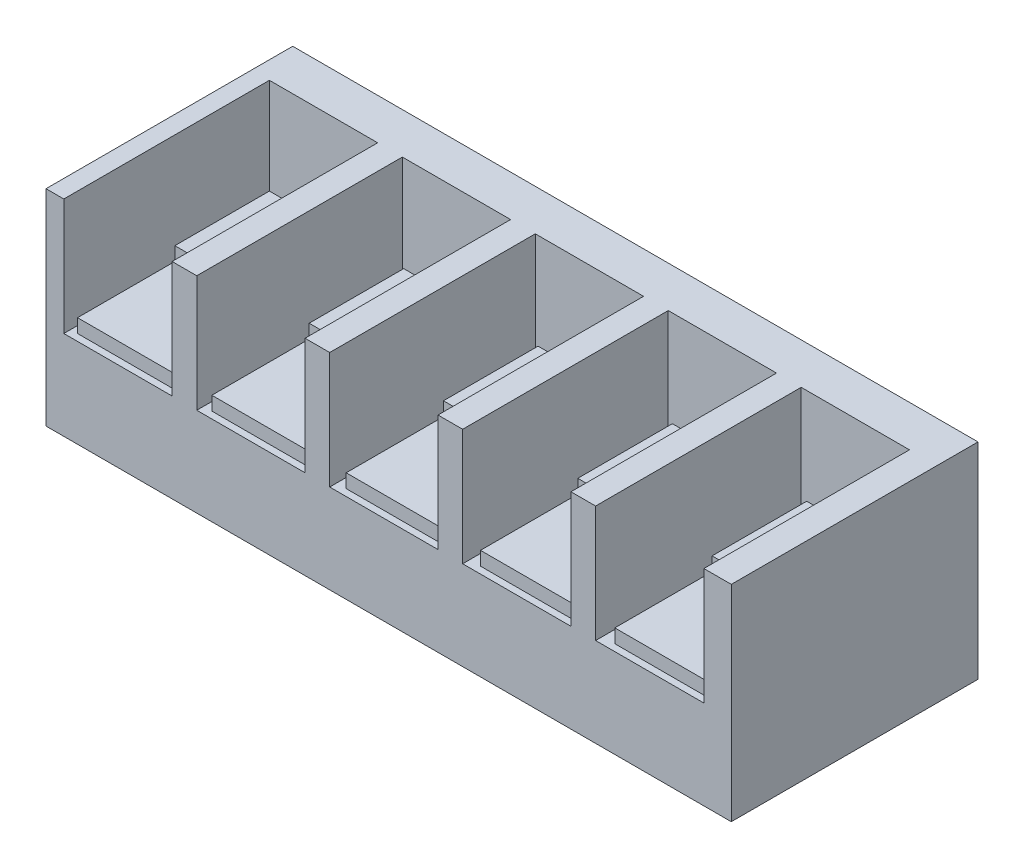
SolidWorks part; units mm, degrees
material "PVC Rigid"
ref_plane "Front Plane" through (0, 0, 0) normal (0, 0, 1) x (1, 0, 0)
ref_plane "Top Plane" through (0, 0, 0) normal (0, 1, 0) x (1, 0, 0)
ref_plane "Right Plane" through (0, 0, 0) normal (1, 0, 0) x (0, 0, -1)
sketch "Sketch1" plane through (0, 0, 0) normal (0, 1, 0) x (1, 0, 0)
  line L1 (25, -9) -> (-25, -9)
  line L2 (25, -9) -> (25, 9)
  line L3 (25, 9) -> (-25, 9)
  line L4 (-25, -9) -> (-25, 9)
  point P0 (0, 0)
  dimension "D1" = 50
  dimension "D2" = 18
extrude "Boss-Extrude1" add sketch "Sketch1" along normal blind 15
sketch "Sketch2" plane through (0, 0, 9) normal (0, 0, 1) x (1, 0, 0)
  line L0 (-25, 15) -> (25, 15) construction
  line L1 (-23.7, 15) -> (-15.8, 15)
  line L2 (-23.7, 15) -> (-23.7, 6.5)
  line L3 (-23.7, 6.5) -> (-15.8, 6.5)
  line L4 (-15.8, 15) -> (-15.8, 6.5)
  line L5 (-25, 15) -> (-25, 0) construction
  line L6 (-14, 15) -> (-6.1, 15)
  line L7 (-14, 15) -> (-14, 6.5)
  line L8 (-14, 6.5) -> (-6.1, 6.5)
  line L9 (-6.1, 15) -> (-6.1, 6.5)
  line L10 (-4.3, 15) -> (3.6, 15)
  line L11 (-4.3, 15) -> (-4.3, 6.5)
  line L12 (-4.3, 6.5) -> (3.6, 6.5)
  line L13 (3.6, 15) -> (3.6, 6.5)
  line L14 (5.4, 15) -> (13.3, 15)
  line L15 (5.4, 15) -> (5.4, 6.5)
  line L16 (5.4, 6.5) -> (13.3, 6.5)
  line L17 (13.3, 15) -> (13.3, 6.5)
  line L18 (15.1, 15) -> (23, 15)
  line L19 (15.1, 15) -> (15.1, 6.5)
  line L20 (15.1, 6.5) -> (23, 6.5)
  line L21 (23, 15) -> (23, 6.5)
  dimension "D1" = 1.3
  dimension "D2" = 7.9
  dimension "D3" = 8.5
  dimension "D4" = 5
extrude "Cut-Extrude1" cut sketch "Sketch2" against normal offset from surface (15 mm away) 3 up to face at (0, 7.5, -9)
sketch "Sketch3" plane through (0, 0, 0) normal (0, -1, 0) x (1, 0, 0)
  line L8 (-23.5, 7.5) -> (-23.5, -7.5)
  line L9 (-23.5, -7.5) -> (23.5, -7.5)
  line L10 (23.5, -7.5) -> (23.5, 7.5)
  line L11 (23.5, 7.5) -> (-23.5, 7.5)
  line L12 (-23.5, 7.5) -> (-23.5, -7.5)
  line L13 (-23.5, -7.5) -> (23.5, -7.5)
  line L14 (23.5, -7.5) -> (23.5, 7.5)
  line L15 (23.5, 7.5) -> (-23.5, 7.5)
  dimension "D1" = 1.5
extrude "Cut-Extrude2" cut sketch "Sketch3" against normal blind 4
sketch "Sketch4" plane through (0, 6.5, 0) normal (0, 1, 0) x (1, 0, 0)
  line L8 (-16.3, 5.5) -> (-23.2, 5.5)
  line L9 (-23.2, 5.5) -> (-23.2, -8.5)
  line L10 (-23.2, -8.5) -> (-16.3, -8.5)
  line L11 (-16.3, -8.5) -> (-16.3, 5.5)
  line L12 (-16.3, 5.5) -> (-23.2, 5.5)
  line L13 (-23.2, 5.5) -> (-23.2, -8.5)
  line L14 (-23.2, -8.5) -> (-16.3, -8.5)
  line L15 (-16.3, -8.5) -> (-16.3, 5.5)
  circle A0 centre (-19.75, 2.05) radius 1.5
  dimension "D2" = 3.45
  dimension "D3" = 6.9
  dimension "D1" = 0.5
extrude "Boss-Extrude2" add sketch "Sketch4" along normal blind 1
pattern_linear "LPattern1" count 5 spacing 9.8 along (1, 0, 0) of "Boss-Extrude2"
sketch "Sketch5" plane through (0, 7.5, 0) normal (0, 1, 0) x (1, 0, 0)
  line L0 (-16.3, -8.5) -> (-16.3, 5.5) construction
  line L1 (-23.2, 5.5) -> (-16.3, 5.5)
  line L2 (-23.2, 5.5) -> (-23.2, -1.4)
  line L3 (-23.2, -1.4) -> (-16.3, -1.4)
  line L4 (-16.3, 5.5) -> (-16.3, -1.4)
  circle A0 centre (-19.75, 2.05) radius 1.5
extrude "Boss-Extrude3" add sketch "Sketch5" along normal blind 1
pattern_linear "LPattern2" count 5 spacing 9.8 along (1, 0, 0) of "Boss-Extrude3"
